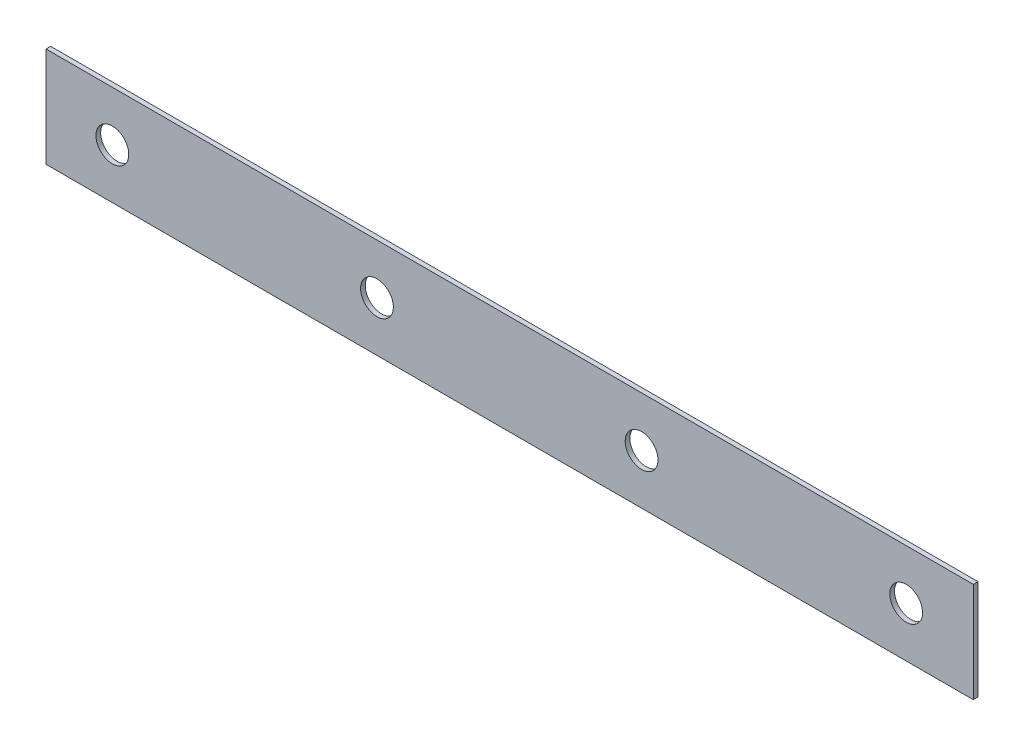
SolidWorks part; units mm, degrees
ref_plane "Front Plane" through (0, 0, 0) normal (0, 0, 1) x (1, 0, 0)
ref_plane "Top Plane" through (0, 0, 0) normal (0, 1, 0) x (1, 0, 0)
ref_plane "Right Plane" through (0, 0, 0) normal (1, 0, 0) x (0, 0, -1)
sketch "Esquisse1" plane through (0, 0, 0) normal (0, 0, 1) x (1, 0, 0)
  line L1 (594, 64) -> (0, 64)
  line L2 (594, 64) -> (594, 0)
  line L3 (594, 0) -> (0, 0)
  line L4 (0, 64) -> (0, 0)
  line L5 (594, 64) -> (0, 0) construction
  line L6 (594, 0) -> (0, 64) construction
  circle A0 centre (42.5, 32) radius 10.5
  circle A2 centre (381.5, 32) radius 10.5
  circle A3 centre (551, 32) radius 10.5
  circle A4 centre (212, 32) radius 10.5
  point P0 (297, 32)
  dimension "D3" = 21
  dimension "D5" = 21
  dimension "D1" = 594
  dimension "D2" = 64
  dimension "D4" = 42.5
  dimension "D6" = 32
  dimension "D7" = 32
  dimension "D8" = 169.5
  dimension "D9" = 169.5
  dimension "D10" = 169.5
  dimension "D11" = 32
  dimension "D12" = 32
extrude "Boss.-Extru.1" add sketch "Esquisse1" along normal blind 3
